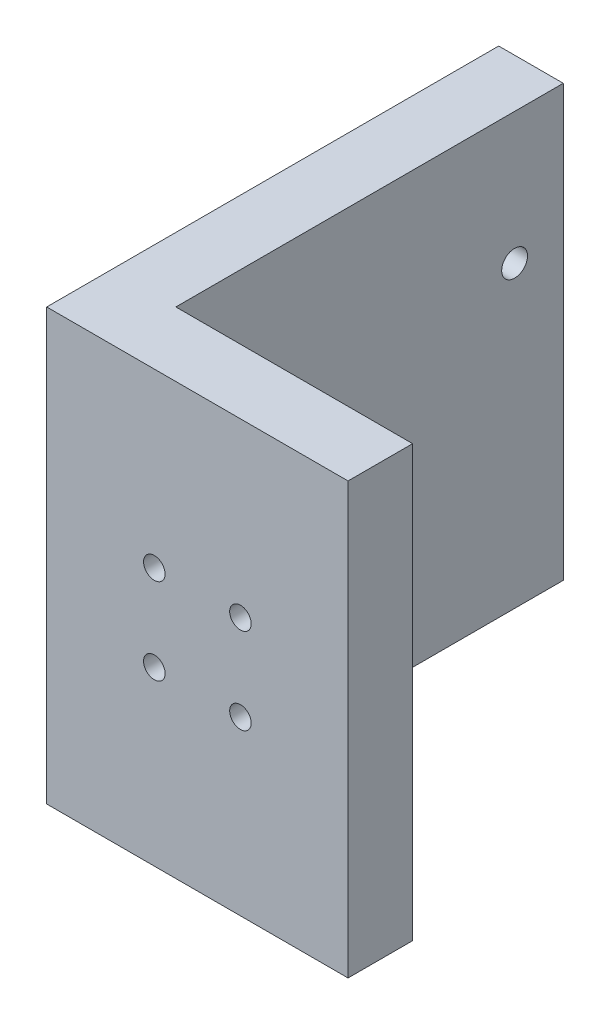
SolidWorks part; units mm, degrees
material "PLA"
ref_plane "Front" through (0, 0, 0) normal (0, 0, 1) x (1, 0, 0)
ref_plane "Top" through (0, 0, 0) normal (0, 1, 0) x (1, 0, 0)
ref_plane "Right" through (0, 0, 0) normal (1, 0, 0) x (0, 0, -1)
other "Configuration Table"
sketch "Esquisse1" plane through (0, 0, 0) normal (0, 1, 0) x (1, 0, 0)
  line L5 (0, 0) -> (35, 0)
  line L6 (0, 0) -> (0, 7.5)
  line L7 (0, 7.5) -> (35, 7.5)
  line L8 (35, 0) -> (35, 7.5)
  line L9 (0, 7.5) -> (7.5, 7.5)
  line L10 (0, 7.5) -> (0, 52.5)
  line L11 (0, 52.5) -> (7.5, 52.5)
  line L12 (7.5, 7.5) -> (7.5, 52.5)
  dimension "D1" = 45
  dimension "D2" = 7.5
  dimension "D3" = 7.5
  dimension "D4" = 35
extrude "Boss.-Extru.1" add sketch "Esquisse1" along normal blind 50
sketch "Esquisse2" plane through (0, 0, 0) normal (0, 0, 1) x (1, 0, 0)
  line L0 (0, 50) -> (35, 50) construction
  line L7 (35, 50) -> (35, 0) construction
  line L8 (12.5, 30) -> (22.5, 30)
  line L9 (12.5, 30) -> (12.5, 20)
  line L10 (12.5, 20) -> (22.5, 20)
  line L11 (22.5, 30) -> (22.5, 20)
  line L12 (12.5, 30) -> (22.5, 20) construction
  line L13 (12.5, 20) -> (22.5, 30) construction
  circle A6 centre (22.5, 30) radius 1.25
  circle A7 centre (22.5, 20) radius 1.25
  circle A8 centre (12.5, 20) radius 1.25
  circle A9 centre (12.5, 30) radius 1.25
  point P1 (17.5, 25)
  point P6 (17.5, 50)
  point P10 (35, 25)
  dimension "D2" = 10
  dimension "D1" = 2.5
extrude "Enlèv. mat.-Extru.1" cut sketch "Esquisse2" against normal blind 37.5
sketch "Esquisse3" plane through (7.5, 0, 0) normal (-1, 0, 0) x (0, 0, 1)
  line L4 (-7.5, 50) -> (-52.5, 50) construction
  line L5 (-52.5, 50) -> (-52.5, 0) construction
  line L6 (-46.8442, 34.725) -> (-30, 25) construction
  line L7 (-30, 25) -> (-30, 5.55) construction
  line L8 (-30, 25) -> (-13.1558, 34.725) construction
  circle A4 centre (-30, 25) radius 19.45
  circle A5 centre (-30, 5.55) radius 1.5
  circle A6 centre (-46.8442, 34.725) radius 1.5
  circle A7 centre (-13.1558, 34.725) radius 1.5
  point P5 (-30, 50)
  point P8 (-52.5, 25)
  dimension "D2" = 3
  dimension "D1" = 38.9
  dimension "D3" = 120
  dimension "D4" = 120
extrude "Enlèv. mat.-Extru.2" cut sketch "Esquisse3" along normal blind 13.5 contours A5 A4 | A5 A4
